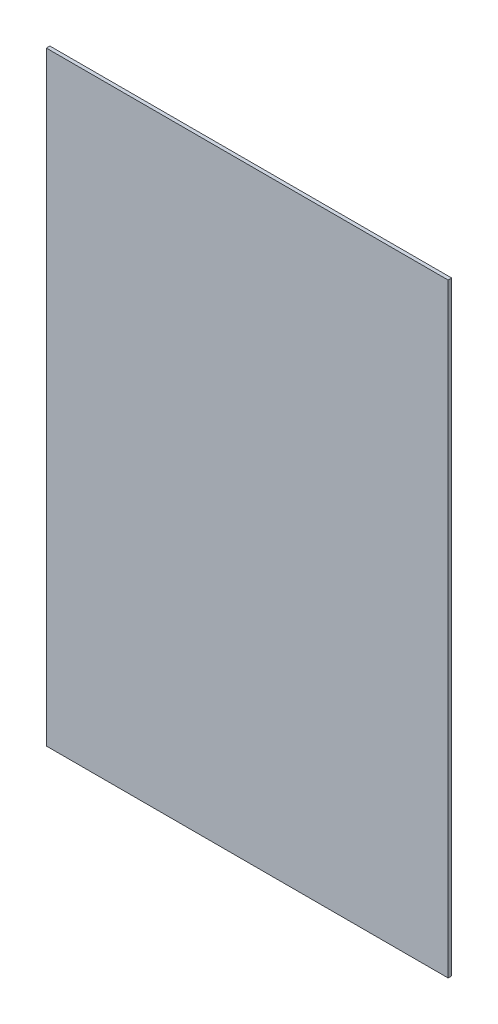
SolidWorks part; units mm, degrees
material "6061-T6 (SS)"
ref_plane "Alzado" through (0, 0, 0) normal (0, 0, 1) x (1, 0, 0)
ref_plane "Planta" through (0, 0, 0) normal (0, 1, 0) x (1, 0, 0)
ref_plane "Vista lateral" through (0, 0, 0) normal (1, 0, 0) x (0, 0, -1)
sketch "Sketch2" plane through (0, 0, 0) normal (0, 0, 1) x (1, 0, 0)
  line L1 (-113, 170) -> (113, 170)
  line L2 (-113, 170) -> (-113, -170)
  line L3 (-113, -170) -> (113, -170)
  line L4 (113, 170) -> (113, -170)
  line L5 (-113, 170) -> (113, -170) construction
  line L6 (-113, -170) -> (113, 170) construction
  point P0 (0, 0)
  dimension "D1" = 340
  dimension "D2" = 226
extrude "Boss-Extrude1" add sketch "Sketch2" along normal blind 2
